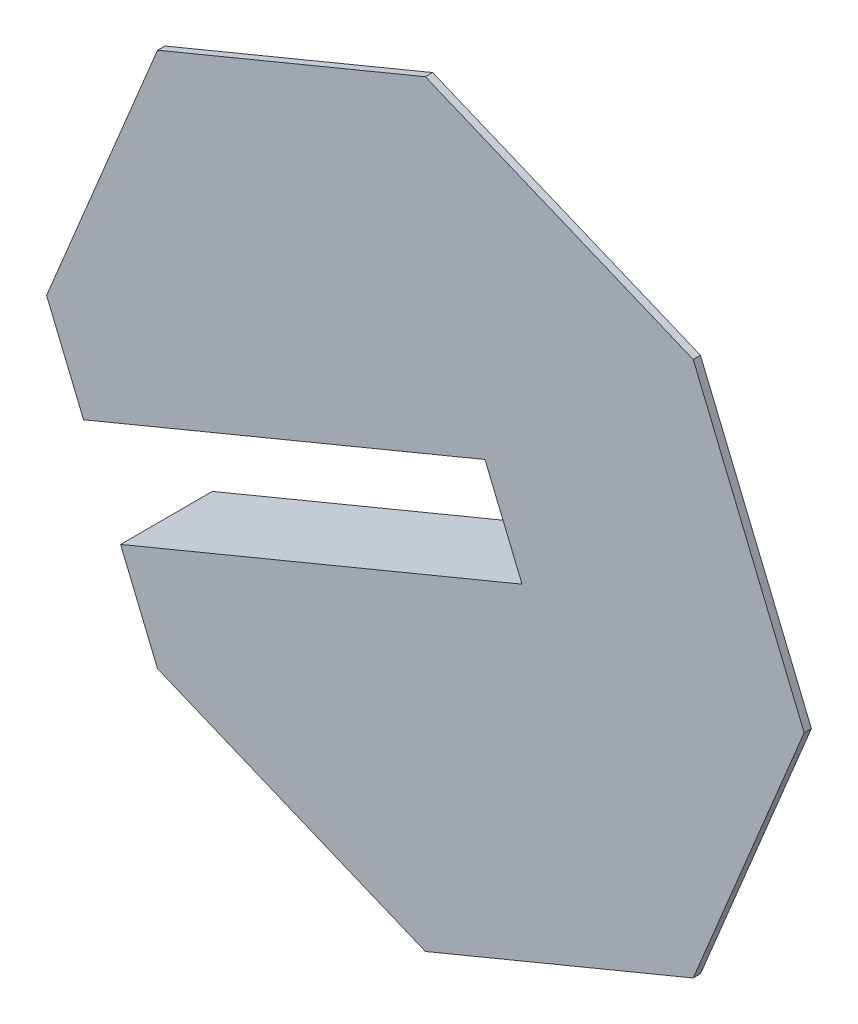
SolidWorks part; units mm, degrees
material "1023 Carbon Steel Sheet (SS)"
ref_plane "Front Plane" through (0, 0, 0) normal (1, 0, 0) x (0, 1, 0)
ref_plane "Top Plane" through (0, 0, 0) normal (0, 0, 1) x (0, 1, 0)
ref_plane "Right Plane" through (0, 0, 0) normal (0, 1, 0) x (-1, 0, 0)
sketch "Sketch6" plane through (0, 0, 0) normal (0, 0, 1) x (0, 1, 0)
  line L1 (156.7876, 0) -> (110.8655, 110.8655)
  line L2 (110.8655, 110.8655) -> (0, 156.7876)
  line L3 (0, 156.7876) -> (-36.9228, 141.4936)
  line L4 (-110.8655, 110.8655) -> (-156.7876, 0)
  line L5 (-156.7876, 0) -> (-110.8655, -110.8655)
  line L6 (-110.8655, -110.8655) -> (0, -156.7876)
  line L7 (0, -156.7876) -> (110.8655, -110.8655)
  line L8 (110.8655, -110.8655) -> (156.7876, 0)
  line L9 (-73.9427, 126.1595) -> (-5.116, -40.0028)
  line L10 (-5.116, -40.0028) -> (31.9038, -24.6687)
  line L11 (31.9038, -24.6687) -> (-36.9228, 141.4936)
  line L12 (-73.9427, 126.1595) -> (-110.8655, 110.8655)
  circle A0 centre (0, 0) radius 144.8528 construction
  dimension "D3" = 35
  dimension "D1" = 120
  dimension "D2" = 40.07
  dimension "D4" = 20.035
extrude "Boss-Extrude4" add sketch "Sketch6" along normal blind 3 from offset 0 contours L1 L2 L3 L11 L10 L9 L12 L4 L5 L6 L7 L8
sketch "Sketch7" plane through (-133.8265, -55.4328, 0) normal (-0.9239, -0.3827, 0) x (0.3827, -0.9239, 0)
  line L1 (20.035, 0) -> (23.035, 0)
  line L2 (20.035, 0) -> (20.035, -35)
  line L3 (20.035, -35) -> (23.035, -35)
  line L4 (23.035, 0) -> (23.035, -35)
  dimension "D1" = 3
  dimension "D2" = 35
extrude "Boss-Extrude5" add sketch "Sketch7" against normal up to surface (446.2643 mm away)
